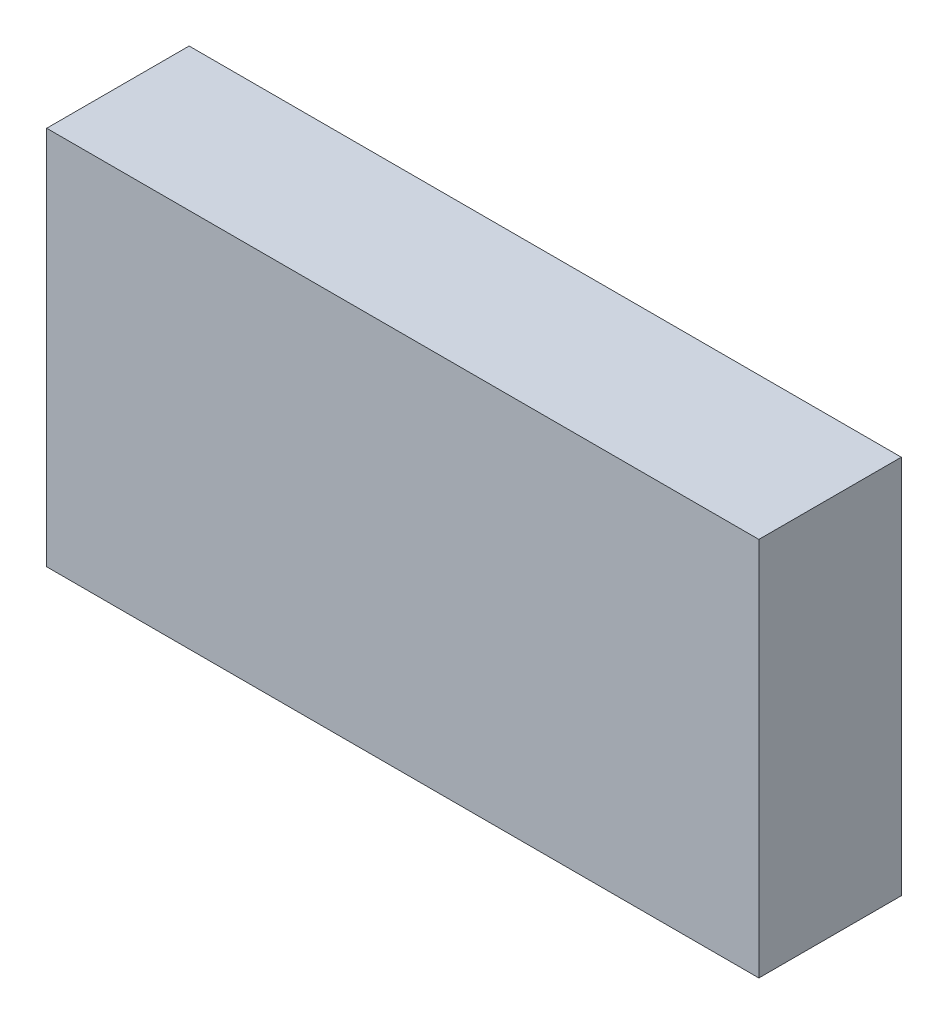
SolidWorks part; units mm, degrees
ref_plane "Front Plane" through (0, 0, 0) normal (0, 0, 1) x (1, 0, 0)
ref_plane "Top Plane" through (0, 0, 0) normal (0, 1, 0) x (1, 0, 0)
ref_plane "Right Plane" through (0, 0, 0) normal (1, 0, 0) x (0, 0, -1)
other "Configuration Table"
sketch "Sketch1" plane through (0, 0, 0) normal (0, 0, 1) x (1, 0, 0)
  line L1 (596, 290) -> (611, 290)
  line L2 (596, 290) -> (596, 298)
  line L3 (596, 298) -> (611, 298)
  line L4 (611, 290) -> (611, 298)
extrude "CEK_1L_miknatis_15x8x3_1" add sketch "Sketch1" against normal blind 3 separate body
